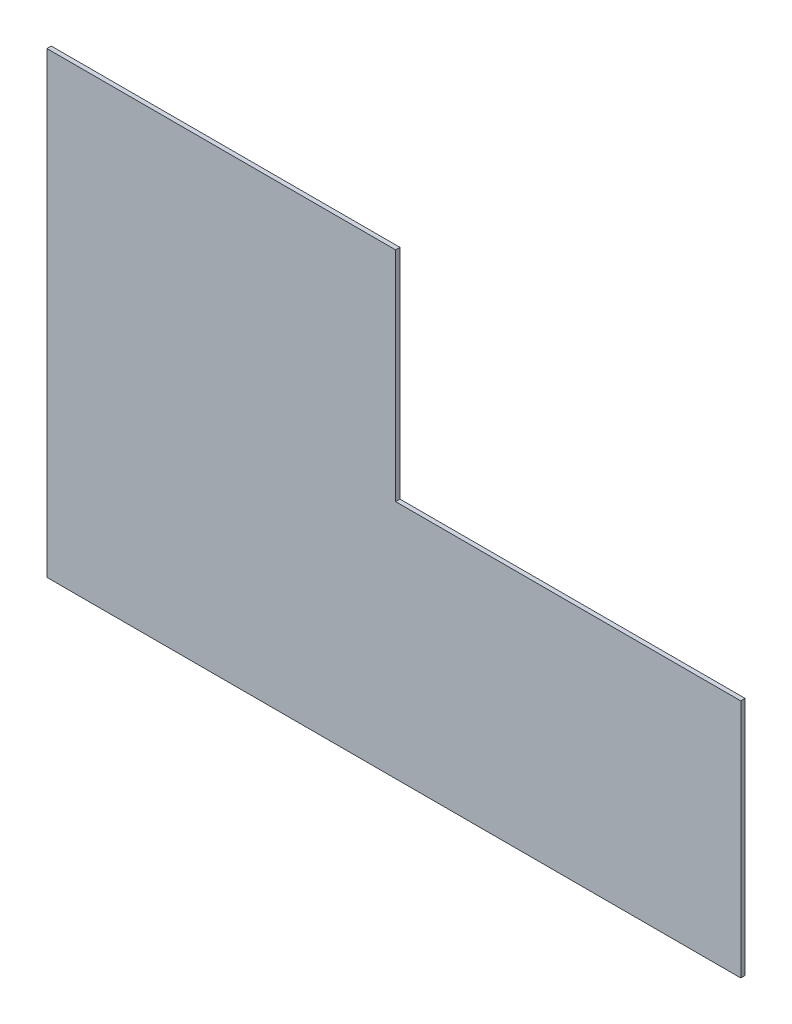
SolidWorks part; units mm, degrees
ref_plane "Front Plane" through (0, 0, 0) normal (0, 0, 1) x (1, 0, 0)
ref_plane "Top Plane" through (0, 0, 0) normal (0, 1, 0) x (1, 0, 0)
ref_plane "Right Plane" through (0, 0, 0) normal (1, 0, 0) x (0, 0, -1)
sketch "Sketch1" plane through (0, 0, 0) normal (0, 0, 1) x (1, 0, 0)
  line L0 (0, 0) -> (479.5, 0)
  line L1 (479.5, 0) -> (479.5, 165.84)
  line L2 (479.5, 165.84) -> (241, 165.84)
  line L3 (241, 165.84) -> (241, 316.5)
  line L4 (241, 316.5) -> (0, 316.5)
  line L5 (0, 316.5) -> (0, 0)
  dimension "D1" = 479.5
  dimension "D2" = 165.84
  dimension "D3" = 238.5
  dimension "D4" = 316.5
extrude "Boss-Extrude1" add sketch "Sketch1" along normal blind 3
